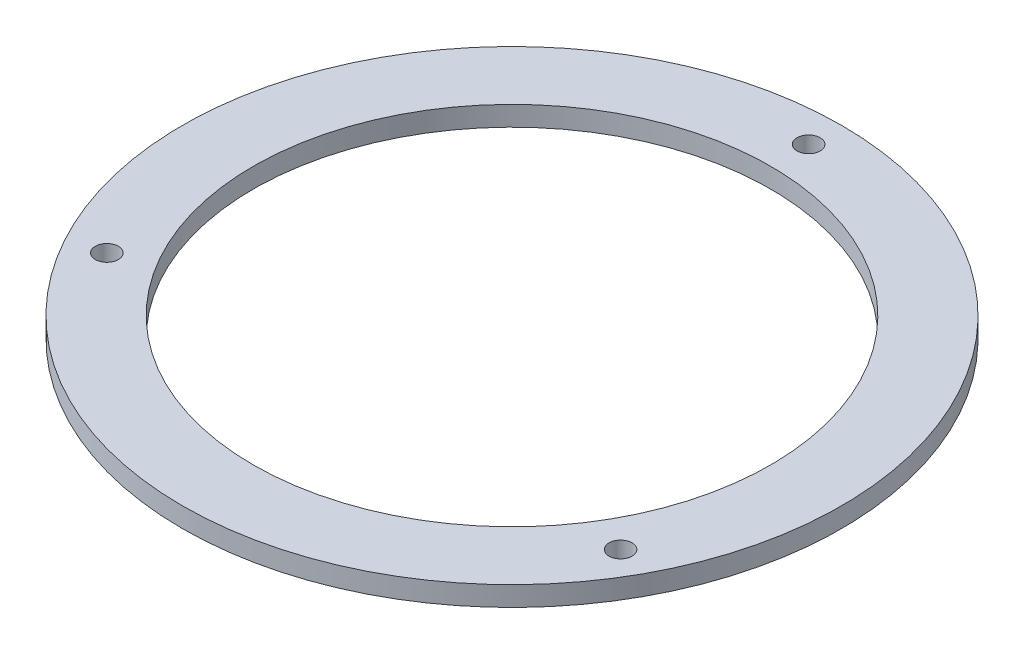
SolidWorks part; units mm, degrees
ref_plane "Front Plane" through (0, 0, 0) normal (0, 0, 1) x (1, 0, 0)
ref_plane "Top Plane" through (0, 0, 0) normal (0, 1, 0) x (1, 0, 0)
ref_plane "Right Plane" through (0, 0, 0) normal (1, 0, 0) x (0, 0, -1)
sketch "Sketch1" plane through (0, 0, 0) normal (0, 1, 0) x (1, 0, 0)
  circle A0 centre (0, 0) radius 39.25
  circle A1 centre (0, 0) radius 50
  circle A2 centre (0, 0) radius 45 construction
  circle A3 centre (0, 45) radius 1.75
  circle A4 centre (38.9711, -22.5) radius 1.75
  circle A5 centre (-38.9711, -22.5) radius 1.75
  point P13 (0, 0)
  dimension "D1" = 100
  dimension "D2" = 78.5
  dimension "D3" = 90
  dimension "D4" = 3.5
  dimension "D5" = 3
extrude "Boss-Extrude1" add sketch "Sketch1" along normal blind 3
